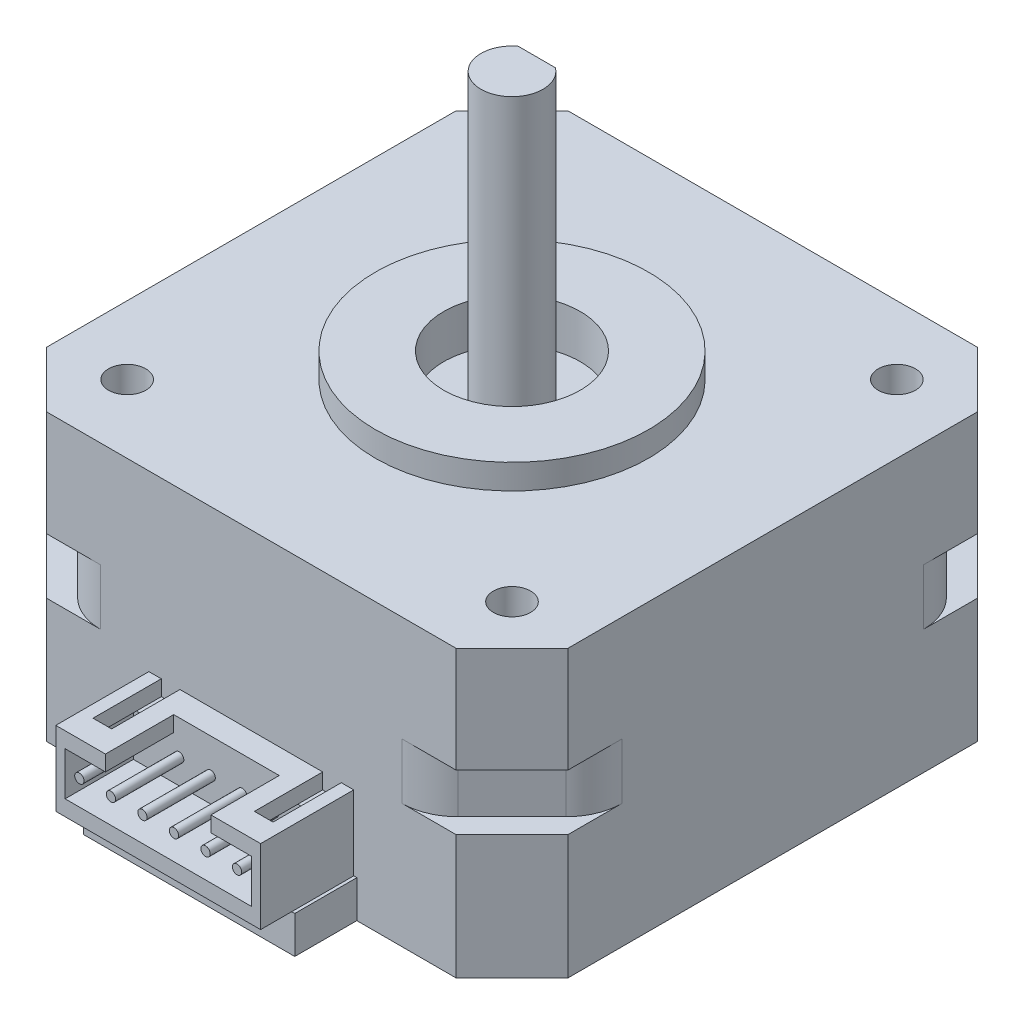
SolidWorks part; units mm, degrees
ref_plane "Front Plane" through (0, 0, 0) normal (0, 0, 1) x (1, 0, 0)
ref_plane "Top Plane" through (0, 0, 0) normal (0, 1, 0) x (1, 0, 0)
ref_plane "Right Plane" through (0, 0, 0) normal (1, 0, 0) x (0, 0, -1)
sketch "Sketch1" plane through (0, 0, 0) normal (0, 1, 0) x (1, 0, 0)
  line L0 (-21, 16.5) -> (-16.5, 21)
  line L1 (-16.5, -21) -> (16.5, -21)
  line L2 (-21, -16.5) -> (-21, 16.5)
  line L3 (-16.5, 21) -> (16.5, 21)
  line L4 (21, -16.5) -> (21, 16.5)
  line L5 (-21, -21) -> (21, 21) construction
  line L6 (-21, 21) -> (21, -21) construction
  line L7 (16.5, 21) -> (21, 16.5)
  line L8 (16.5, -21) -> (21, -16.5)
  line L9 (-21, -16.5) -> (-16.5, -21)
  point P0 (0, 0)
  dimension "D1" = 42
  dimension "D3" = 42
extrude "Boss-Extrude1" add sketch "Sketch1" along normal blind 10
sketch "Sketch2" plane through (0, 10, 0) normal (0, 1, 0) x (1, 0, 0)
  line L0 (-15.318, 19.682) -> (-19.682, 15.318)
  line L5 (12.136, -21) -> (-12.136, -21)
  line L6 (21, -12.136) -> (21, 12.136)
  line L7 (12.136, 21) -> (-12.136, 21)
  line L8 (-21, -12.136) -> (-21, 12.136)
  line L9 (21, -21) -> (-21, 21) construction
  line L10 (21, 21) -> (-21, -21) construction
  line L11 (19.682, 15.318) -> (15.318, 19.682)
  line L12 (19.682, -15.318) -> (15.318, -19.682)
  line L13 (-15.318, -19.682) -> (-19.682, -15.318)
  arc A0 (-19.682, -15.318) -> (-21, -12.136) centre (-16.5, -12.136) cw
  arc A1 (-15.318, -19.682) -> (-12.136, -21) centre (-12.136, -16.5) ccw
  arc A2 (15.318, -19.682) -> (12.136, -21) centre (12.136, -16.5) cw
  arc A3 (19.682, -15.318) -> (21, -12.136) centre (16.5, -12.136) ccw
  arc A4 (19.682, 15.318) -> (21, 12.136) centre (16.5, 12.136) cw
  arc A5 (15.318, 19.682) -> (12.136, 21) centre (12.136, 16.5) ccw
  arc A6 (-19.682, 15.318) -> (-21, 12.136) centre (-16.5, 12.136) ccw
  arc A7 (-15.318, 19.682) -> (-12.136, 21) centre (-12.136, 16.5) cw
  point P0 (0, 0)
  point P17 (-21, -14)
  point P20 (-14, -21)
  point P23 (14, -21)
  point P26 (21, -14)
  point P29 (21, 14)
  point P32 (14, 21)
  point P35 (-21, 14)
  point P38 (-14, 21)
  dimension "D3" = 4.5
  dimension "D1" = 42
  dimension "D2" = 42
extrude "Boss-Extrude3" add sketch "Sketch2" along normal blind 4.5
sketch "Sketch4" plane through (0, 14.5, 0) normal (0, 1, 0) x (1, 0, 0)
  line L0 (-16.5, 21) -> (-21, 16.5)
  line L1 (16.5, -21) -> (-16.5, -21)
  line L2 (21, -16.5) -> (21, 16.5)
  line L3 (16.5, 21) -> (-16.5, 21)
  line L4 (-21, -16.5) -> (-21, 16.5)
  line L5 (21, -21) -> (-21, 21) construction
  line L6 (21, 21) -> (-21, -21) construction
  line L7 (21, 16.5) -> (16.5, 21)
  line L8 (-16.5, -21) -> (-21, -16.5)
  line L9 (21, -16.5) -> (16.5, -21)
  point P0 (0, 0)
  dimension "D1" = 42
  dimension "D3" = 42
extrude "Boss-Extrude4" add sketch "Sketch4" along normal blind 8.5
sketch "Sketch5" plane through (0, 23, 0) normal (0, 1, 0) x (1, 0, 0)
  circle A0 centre (0, 0) radius 11
  dimension "D1" = 22
extrude "Boss-Extrude5" add sketch "Sketch5" along normal blind 2
sketch "Sketch6" plane through (0, 23, 0) normal (0, 1, 0) x (1, 0, 0)
  line L0 (0, -21) -> (0, 21) construction
  line L1 (16.5, 21) -> (-16.5, 21) construction
  line L2 (21, 0) -> (-21, 0) construction
  line L3 (-21, 16.5) -> (-21, -16.5) construction
  circle A0 centre (-15.5, 15.5) radius 1.5
  circle A2 centre (15.5, 15.5) radius 1.5
  circle A3 centre (15.5, -15.5) radius 1.5
  circle A4 centre (-15.5, -15.5) radius 1.5
  point P6 (0, 0)
  point P12 (0, 0)
  point P22 (0, 0)
  dimension "D1" = 3
  dimension "D2" = 31
  dimension "D3" = 31
  dimension "D4" = 4
extrude "Cut-Extrude1" cut sketch "Sketch6" against normal up to next
sketch "Sketch7" plane through (0, 25, 0) normal (0, 1, 0) x (1, 0, 0)
  circle A0 centre (0, 0) radius 5.5
  dimension "D1" = 11
extrude "Cut-Extrude2" cut sketch "Sketch7" against normal blind 3.5
sketch "Sketch8" plane through (0, 21.5, 0) normal (0, 1, 0) x (1, 0, 0)
  circle A0 centre (0, 0) radius 2.5
  dimension "D1" = 5
extrude "Boss-Extrude6" add sketch "Sketch8" along normal blind 3.5
sketch "Sketch9" plane through (0, 25, 0) normal (0, 1, 0) x (1, 0, 0)
  line L0 (0, 0) -> (0, -2.5) construction
  line L1 (-1.5, 2) -> (1.5, 2)
  circle A1 centre (0, 0) radius 2.5
  arc A2 (-1.5, 2) -> (1.5, 2) centre (0, 0) ccw
  dimension "D2" = 4.5
  dimension "D1" = 0
extrude "Boss-Extrude7" add sketch "Sketch9" along normal blind 19.5
sketch "Sketch10" plane through (0, 0, 0) normal (0, -1, 0) x (1, 0, 0)
  circle A0 centre (-15.5, 15.5) radius 3.5
  circle A1 centre (15.5, 15.5) radius 3.5
  circle A2 centre (15.5, -15.5) radius 3.5
  circle A3 centre (-15.5, -15.5) radius 3.5
  point P12 (0, 0)
  dimension "D1" = 7
  dimension "D3" = 31
  dimension "D2" = 4
extrude "Cut-Extrude3" cut sketch "Sketch10" against normal blind 3
sketch "Sketch11" plane through (0, 0, 21) normal (0, 0, 1) x (1, 0, 0)
  line L0 (8.5, 3) -> (8.5, 0)
  line L1 (8.5, 3) -> (-8.5, 3)
  line L2 (8.5, 0) -> (-8.5, 0)
  line L3 (-8.5, 3) -> (-8.5, 0)
  line L4 (8.5, 3) -> (-8.5, 0) construction
  line L5 (8.5, 0) -> (-8.5, 3) construction
  point P1 (0, 1.5)
  point P2 (0, 0)
  dimension "D1" = 3
  dimension "D2" = 17
extrude "Boss-Extrude8" add sketch "Sketch11" along normal blind 5
sketch "Sketch12" plane through (0, 0, 21) normal (0, 0, 1) x (1, 0, 0)
  line L0 (-8.25, 3) -> (8.25, 3)
  line L1 (-8.25, 3) -> (-8.25, 9)
  line L2 (8.25, 3) -> (8.25, 9)
  line L3 (-8.25, 9) -> (8.25, 9)
  line L4 (8.5, 3) -> (-8.5, 3) construction
  point P0 (0, 3)
  dimension "D1" = 6
  dimension "D2" = 16.5
extrude "Boss-Extrude9" add sketch "Sketch12" along normal blind 7.5
sketch "Sketch13" plane through (0, 0, 28.5) normal (0, 0, 1) x (1, 0, 0)
  line L1 (-7.5, 4.25) -> (7.5, 4.25)
  line L2 (-7.5, 4.25) -> (-7.5, 7.75)
  line L3 (-7.5, 7.75) -> (7.5, 7.75)
  line L4 (7.5, 4.25) -> (7.5, 7.75)
  line L5 (-7.5, 4.25) -> (7.5, 7.75) construction
  line L6 (-7.5, 7.75) -> (7.5, 4.25) construction
  point P0 (0, 6)
  dimension "D1" = 3.5
  dimension "D2" = 15
  dimension "D3" = 6
extrude "Cut-Extrude4" cut sketch "Sketch13" against normal blind 5.5
sketch "Sketch14" plane through (0, 9, 0) normal (0, 1, 0) x (1, 0, 0)
  line L0 (8.25, -28.5) -> (-8.25, -28.5) construction
  line L1 (-4.25, -28.5) -> (4.25, -28.5)
  line L2 (-4.25, -28.5) -> (-4.25, -23)
  line L3 (-4.25, -23) -> (4.25, -23)
  line L4 (4.25, -28.5) -> (4.25, -23)
  line L5 (0, -23) -> (0, -28.5) construction
  line L6 (-4.25, -25.75) -> (4.25, -25.75) construction
  line L7 (-8.25, -28.5) -> (-8.25, -21) construction
  line L8 (8.25, -28.5) -> (8.25, -21) construction
  line L10 (8.25, -21) -> (-8.25, -21) construction
  point P104 (0, -25.75)
  dimension "D1" = 4
  dimension "D2" = 4
  dimension "D3" = 2
extrude "Cut-Extrude5" cut sketch "Sketch14" against normal up to next
sketch "Sketch15" plane through (0, 9, 0) normal (0, 1, 0) x (1, 0, 0)
  line L0 (-16.5, -21) -> (16.5, -21) construction
  line L1 (-7.25, -21) -> (-5.75, -21)
  line L2 (-7.25, -21) -> (-7.25, -26.5)
  line L3 (-7.25, -26.5) -> (-5.75, -26.5)
  line L4 (-5.75, -21) -> (-5.75, -26.5)
  line L5 (-6.5, -26.5) -> (-6.5, -21) construction
  line L6 (-7.25, -23.75) -> (-5.75, -23.75) construction
  line L7 (-4.25, -23) -> (-4.25, -28.5) construction
  line L8 (-4.25, -28.5) -> (-8.25, -28.5) construction
  line L9 (0, 0) -> (0, -28.5) construction
  line L10 (-7.5, -28.5) -> (7.5, -28.5) construction
  line L11 (7.25, -26.5) -> (5.75, -26.5)
  line L12 (5.75, -21) -> (5.75, -26.5)
  line L13 (7.25, -21) -> (5.75, -21)
  line L14 (7.25, -21) -> (7.25, -26.5)
  point P168 (-6.5, -23.75)
  dimension "D1" = 1.5
  dimension "D2" = 1.5
  dimension "D3" = 2
extrude "Cut-Extrude6" cut sketch "Sketch15" against normal up to surface (1.25 mm away) up to face at (-5.875, 7.75, 25.75)
sketch "Sketch16" plane through (0, 0, 23) normal (0, 0, 1) x (1, 0, 0)
  line L0 (0, 0) -> (0, 9) construction
  line L1 (4.25, 9) -> (-4.25, 9) construction
  line L2 (-7.5, 4.25) -> (7.5, 4.25) construction
  circle A0 centre (-1.27, 6.25) radius 0.375
  circle A1 centre (1.27, 6.25) radius 0.375
  circle A2 centre (-3.81, 6.25) radius 0.375
  circle A3 centre (-6.35, 6.25) radius 0.375
  circle A4 centre (3.81, 6.25) radius 0.375
  circle A5 centre (6.35, 6.25) radius 0.375
  dimension "D1" = 0.75
  dimension "D2" = 2.54
  dimension "D3" = 2
  dimension "D4" = 3
  dimension "D5" = 3
extrude "Boss-Extrude10" add sketch "Sketch16" along normal up to surface (5.5 mm away) up to face at (0, 6.7917, 28.5)
